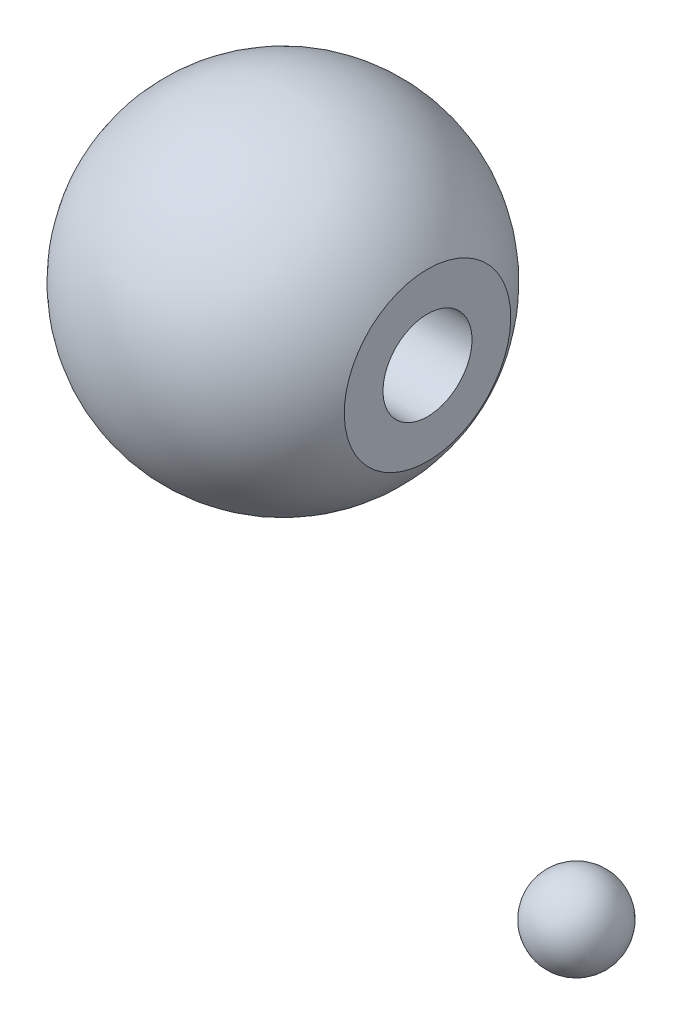
SolidWorks part; units mm, degrees
ref_plane "Front Plane" through (0, 0, 0) normal (0, 0, 1) x (1, 0, 0)
ref_plane "Top Plane" through (0, 0, 0) normal (0, 1, 0) x (1, 0, 0)
ref_plane "Right Plane" through (0, 0, 0) normal (1, 0, 0) x (0, 0, -1)
sketch "Sketch1" plane through (0, 0, 0) normal (0, 0, 1) x (1, 0, 0)
  line L0 (19.5, 0) -> (-22.5, 0)
  line L2 (19.5, 0) -> (19.5, -11.225)
  arc A0 (-22.5, 0) -> (19.5, -11.225) centre (0, 0) ccw
revolve "Revolve1" add sketch "Sketch1" angle 360 about L0
sketch "Sketch2" plane through (19.5, 0, 0) normal (1, 0, 0) x (0, 0, -1)
  line L0 (0, 0) -> (0, 11.225) construction
  circle A0 centre (0, 0) radius 11.225 construction
hole_wizard "M12x1.5 Tapped Hole1" positions "3DSketch2" profile "Sketch3" tap size "M12x1.5" standard "ANSI Metric"
sketch3d "3DSketch2"
  point P0 (19.5, 0, 0)
sketch "Sketch3" plane through (19.5, 0, 0) normal (0, 1, 0) x (0, 0, -1)
  line L0 (0, 0) -> (0, 37.6052)
  line L1 (0, 37.6052) -> (6, 34)
  line L2 (6, 34) -> (6, 0)
  line L5 (6, 0) -> (0, 0)
  line L10 (0, 37.6052) -> (-6, 34) construction
  line L11 (0, -6.35) -> (0, 107.95) construction
  dimension "Tap Drill Dia." = 12
  dimension "Tap Drill Depth" = 34
  dimension "Drill Angle" = 118
cosmetic thread "Hole Thread1"
sketch "Sketch4" plane through (0, 0, 0) normal (0, 1, 0) x (1, 0, 0)
  line L0 (94.2448, -49.073) -> (94.2448, -60.273)
  arc A0 (94.2448, -60.273) -> (94.2448, -49.073) centre (94.2448, -54.673) ccw
revolve "Revolve2" add sketch "Sketch4" angle 360 about L0
